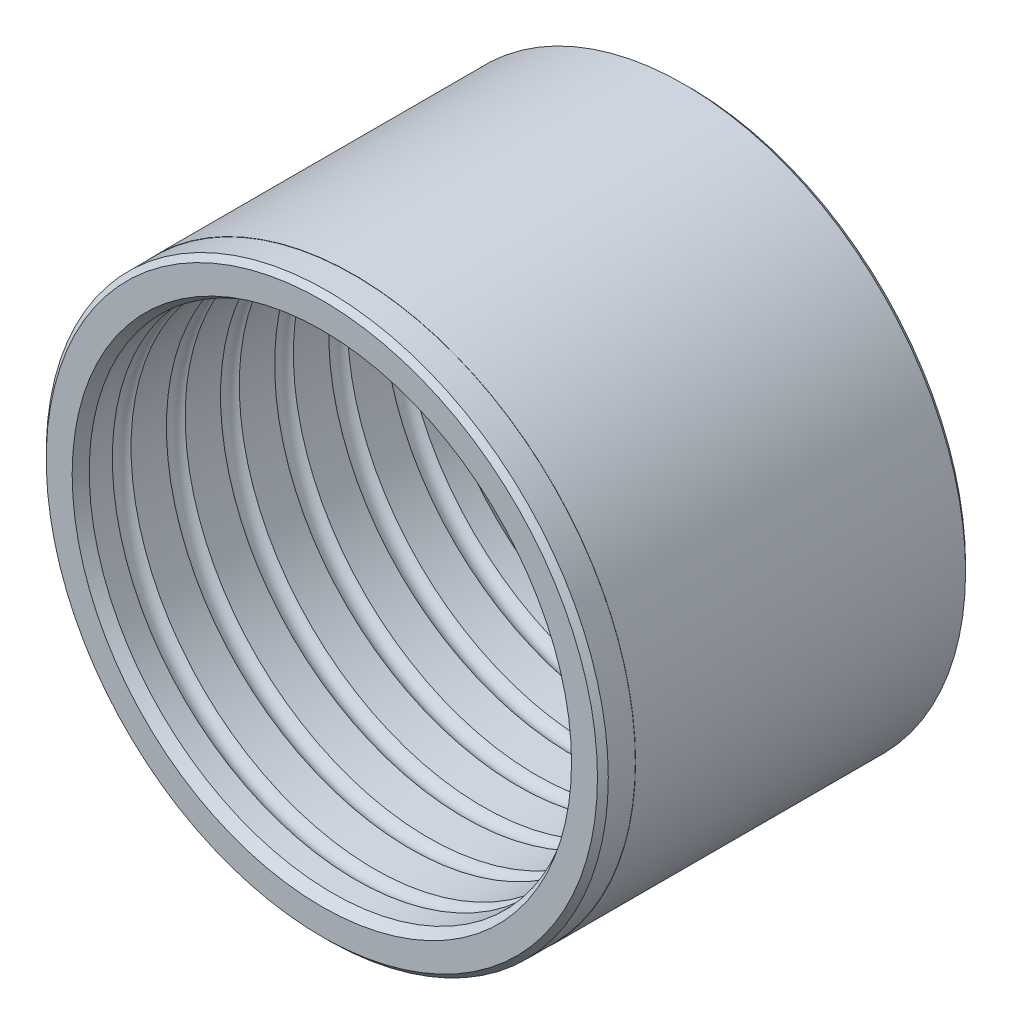
SolidWorks part; units mm, degrees
material "Phosphor bronze 10% D, UNS C52400"
ref_plane "Front" through (0, 0, 0) normal (0, 0, 1) x (1, 0, 0)
ref_plane "Top" through (0, 0, 0) normal (0, 1, 0) x (1, 0, 0)
ref_plane "Right" through (0, 0, 0) normal (1, 0, 0) x (0, 0, -1)
sketch "Sketch1" plane through (0, 0, 0) normal (1, 0, 0) x (0, 0, -1)
  line L0 (0, 0) -> (34, 0) construction
  line L1 (3, 26) -> (33.5, 26)
  line L2 (34, 24.5) -> (34, 25.5)
  line L3 (0, 25.475) -> (0, 23.0774)
  line L4 (3, 26) -> (3, 25.975)
  line L5 (0.5, 25.975) -> (3, 25.975)
  line L6 (0, 25.475) -> (0.5, 25.975)
  line L7 (0, 26) -> (34, 26) construction
  line L8 (0, 25.975) -> (34, 25.975) construction
  line L9 (3, 26) -> (3, 0) construction
  line L10 (0, 26) -> (0, 0) construction
  line L11 (33.5, 26) -> (34, 25.5)
  line L12 (1, 22.5) -> (3.134, 22.5)
  line L13 (0, 22.5) -> (34, 22.5) construction
  line L14 (32, 22.5) -> (34, 24.5)
  line L15 (0, 23.0774) -> (1, 22.5)
  line L16 (4.866, 22.5) -> (8.134, 22.5)
  line L17 (9.866, 22.5) -> (13.134, 22.5)
  line L18 (14.866, 22.5) -> (18.134, 22.5)
  line L19 (19.866, 22.5) -> (23.134, 22.5)
  line L20 (24.866, 22.5) -> (28.134, 22.5)
  line L21 (29.866, 22.5) -> (32, 22.5)
  arc A0 (4.866, 22.5) -> (3.134, 22.5) centre (4, 22) ccw
  arc A1 (9.866, 22.5) -> (8.134, 22.5) centre (9, 22) ccw
  arc A2 (14.866, 22.5) -> (13.134, 22.5) centre (14, 22) ccw
  arc A3 (19.866, 22.5) -> (18.134, 22.5) centre (19, 22) ccw
  arc A4 (24.866, 22.5) -> (23.134, 22.5) centre (24, 22) ccw
  arc A5 (29.866, 22.5) -> (28.134, 22.5) centre (29, 22) ccw
  dimension "D14" = 1
  dimension "D18" = 5
  dimension "D19" = 5
  dimension "D1" = 34
  dimension "D2" = 26
  dimension "D3" = 25.975
  dimension "D4" = 3
  dimension "D5" = 0.5
  dimension "D6" = 45
  dimension "D7" = 0.5
  dimension "D8" = 45
  dimension "D9" = 22.5
  dimension "D10" = 2
  dimension "D11" = 45
  dimension "D12" = 1
  dimension "D13" = 30
  dimension "D15" = 0.5
  dimension "D16" = 4
  dimension "D17" = 6
revolve "Revolve1" add sketch "Sketch1" angle 360 about L0
